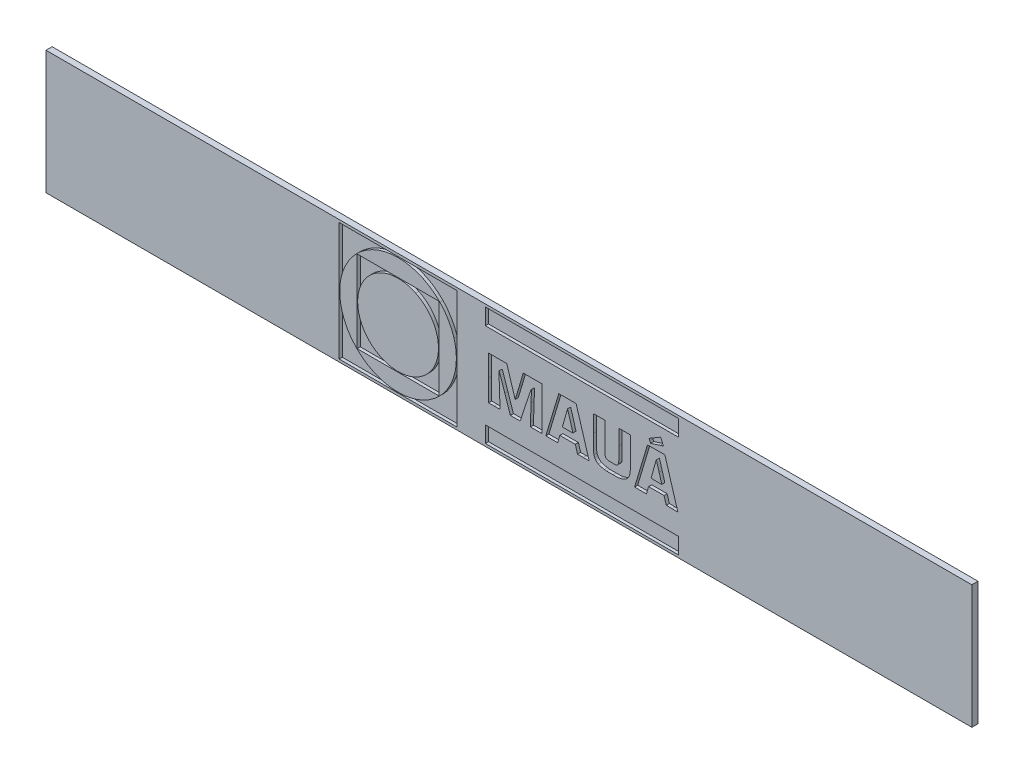
SolidWorks part; units mm, degrees
ref_plane "Front Plane" through (0, 0, 0) normal (0, 0, 1) x (1, 0, 0)
ref_plane "Top Plane" through (0, 0, 0) normal (0, 1, 0) x (1, 0, 0)
ref_plane "Right Plane" through (0, 0, 0) normal (1, 0, 0) x (0, 0, -1)
sketch "Model" plane through (0, 0, 0) normal (0, 0, 1) x (1, 0, 0)
  line L0 (-27.4995, 0.0001) -> (-27.4995, 9.5754)
  line L1 (-27.4995, 9.5754) -> (-17.9397, 9.5754)
  line L2 (-17.9397, 9.5754) -> (-8.3799, 9.5754)
  line L3 (-8.3799, 9.5754) -> (-8.3799, 0.0001)
  line L4 (-8.3799, 0.0001) -> (-8.3799, -9.5752)
  line L5 (-8.3799, -9.5752) -> (-17.9397, -9.5752)
  line L6 (-17.9397, -9.5752) -> (-27.4995, -9.5752)
  line L7 (-27.4995, -9.5752) -> (-27.4995, 0.0001)
  line L8 (-24.5819, -0.0154) -> (-24.5819, 6.6268)
  line L9 (-24.5819, 6.6268) -> (-17.9552, 6.6268)
  line L10 (-17.9552, 6.6268) -> (-11.3286, 6.6268)
  line L11 (-11.3286, 6.6268) -> (-11.3286, -0.0154)
  line L12 (-11.3286, -0.0154) -> (-11.3286, -6.6576)
  line L13 (-11.3286, -6.6576) -> (-17.9552, -6.6576)
  line L14 (-17.9552, -6.6576) -> (-24.5819, -6.6576)
  line L15 (-24.5819, -6.6576) -> (-24.5819, -0.0154)
  line L16 (-17.3141, -6.5322) -> (-17.3145, -6.5322)
  line L17 (-3.8173, -8.2716) -> (-3.8173, -6.968)
  line L18 (-3.8173, -6.968) -> (11.8416, -6.968)
  line L19 (11.8416, -6.968) -> (27.5004, -6.968)
  line L20 (27.5004, -6.968) -> (27.5004, -8.2716)
  line L21 (27.5004, -8.2716) -> (27.5004, -9.5752)
  line L22 (27.5004, -9.5752) -> (11.8416, -9.5752)
  line L23 (11.8416, -9.5752) -> (-3.8173, -9.5752)
  line L24 (-3.8173, -9.5752) -> (-3.8173, -8.2716)
  line L25 (13.6956, 0.6286) -> (13.6856, 3.3678)
  line L26 (13.6856, 3.3678) -> (14.6181, 3.3678)
  line L27 (14.6181, 3.3678) -> (15.5507, 3.3678)
  line L28 (15.5507, 3.3678) -> (15.5507, 0.9359)
  line L29 (17.8163, 0.939) -> (17.8164, 3.3678)
  line L30 (17.8164, 3.3678) -> (18.7476, 3.3678)
  line L31 (18.7476, 3.3678) -> (19.6787, 3.3678)
  line L32 (19.6787, 3.3678) -> (19.6787, 0.8267)
  line L33 (15.83, -3.6287) -> (15.83, -3.6289)
  line L34 (-3.2896, -0.1241) -> (-3.2896, 3.3678)
  line L35 (-3.2896, 3.3678) -> (-1.8168, 3.3678)
  line L36 (-1.8168, 3.3678) -> (-0.3439, 3.3678)
  line L37 (-0.3439, 3.3678) -> (-0.2812, 3.1582)
  line L38 (1.6785, 1.1795) -> (2.3115, 3.3678)
  line L39 (2.3115, 3.3678) -> (3.8254, 3.3678)
  line L40 (3.8254, 3.3678) -> (5.3393, 3.3678)
  line L41 (5.3393, 3.3678) -> (5.3314, -0.1163)
  line L42 (5.3314, -0.1163) -> (5.3236, -3.6004)
  line L43 (5.3236, -3.6004) -> (4.3976, -3.6086)
  line L44 (4.3976, -3.6086) -> (3.4716, -3.6168)
  line L45 (3.4716, -3.6168) -> (3.4957, -2.8481)
  line L46 (2.7012, -0.9465) -> (1.8195, -3.6158)
  line L47 (1.8195, -3.6158) -> (1.0264, -3.6153)
  line L48 (1.0264, -3.6153) -> (0.2333, -3.6148)
  line L49 (0.2333, -3.6148) -> (-0.6628, -0.9459)
  line L50 (-2.3688, -3.6155) -> (-3.2896, -3.6155)
  line L51 (-3.2896, -3.6155) -> (-3.2896, -0.1241)
  line L52 (9.4879, 3.3677) -> (10.8848, 3.3677)
  line L53 (10.8848, 3.3677) -> (11.9445, -0.1144)
  line L54 (12.0529, -3.6159) -> (11.121, -3.6159)
  line L55 (11.121, -3.6159) -> (10.9381, -3.0106)
  line L56 (10.9381, -3.0106) -> (10.7552, -2.4053)
  line L57 (10.7552, -2.4053) -> (9.5013, -2.4131)
  line L58 (9.5013, -2.4131) -> (8.2474, -2.4209)
  line L59 (8.2474, -2.4209) -> (8.077, -3.0184)
  line L60 (8.077, -3.0184) -> (7.9065, -3.6159)
  line L61 (7.9065, -3.6159) -> (6.9448, -3.6159)
  line L62 (6.9448, -3.6159) -> (5.9831, -3.6159)
  line L63 (5.9831, -3.6159) -> (6.0014, -3.5305)
  line L64 (23.8627, 3.3678) -> (25.2635, 3.3678)
  line L65 (25.2635, 3.3678) -> (25.3716, 3.0186)
  line L66 (26.4268, -3.6086) -> (25.4989, -3.6004)
  line L67 (25.4989, -3.6004) -> (25.315, -3.0029)
  line L68 (25.315, -3.0029) -> (25.1311, -2.4054)
  line L69 (25.1311, -2.4054) -> (23.8806, -2.4054)
  line L70 (23.8806, -2.4054) -> (22.63, -2.4054)
  line L71 (22.63, -2.4054) -> (22.5685, -2.6149)
  line L72 (20.3616, -3.6016) -> (20.3616, -3.6017)
  line L73 (23.893, -1.0397) -> (24.7618, -1.0397)
  line L74 (24.7618, -1.0397) -> (24.3326, 0.4537)
  line L75 (22.8219, 4.113) -> (22.6942, 4.3926)
  line L76 (22.6942, 4.3926) -> (23.2117, 4.6981)
  line L77 (-3.8173, 8.2563) -> (-3.8173, 9.5754)
  line L78 (-3.8173, 9.5754) -> (11.8416, 9.5754)
  line L79 (11.8416, 9.5754) -> (27.5004, 9.5754)
  line L80 (27.5004, 9.5754) -> (27.5004, 8.2563)
  line L81 (27.5004, 8.2563) -> (27.5004, 6.9372)
  line L82 (27.5004, 6.9372) -> (11.8416, 6.9372)
  line L83 (11.8416, 6.9372) -> (-3.8173, 6.9372)
  line L84 (-3.8173, 6.9372) -> (-3.8173, 8.2563)
  spline S0 degree 3 poles (-17.0662, -9.4193) (-15.2179, -9.2367) (-13.5182, -8.5448) (-12.0537, -7.3788) knots 0 0 0 0 1 1 1 1
  spline S1 degree 3 poles (-12.0537, -7.3788) (-11.6343, -7.045) (-10.9257, -6.339) (-10.5982, -5.9288) knots 0 0 0 0 1 1 1 1
  spline S2 degree 3 poles (-10.5982, -5.9288) (-8.6491, -3.4876) (-8.0249, -0.3347) (-8.8967, 2.6657) knots 0 0 0 0 1 1 1 1
  spline S3 degree 3 poles (-8.8967, 2.6657) (-9.3024, 4.062) (-10.1261, 5.4633) (-11.1833, 6.5557) knots 0 0 0 0 1 1 1 1
  spline S4 degree 3 poles (-11.1833, 6.5557) (-12.7357, 8.1599) (-14.7556, 9.1433) (-17.0086, 9.3919) knots 0 0 0 0 1 1 1 1
  spline S5 degree 3 poles (-17.0086, 9.3919) (-17.487, 9.4446) (-18.5269, 9.4359) (-19.0416, 9.3748) knots 0 0 0 0 1 1 1 1
  spline S6 degree 3 poles (-19.0416, 9.3748) (-21.9037, 9.035) (-24.4371, 7.4258) (-25.982, 4.9663) knots 0 0 0 0 1 1 1 1
  spline S7 degree 3 poles (-25.982, 4.9663) (-26.5362, 4.084) (-26.9635, 3.0463) (-27.1898, 2.0331) knots 0 0 0 0 1 1 1 1
  spline S8 degree 3 poles (-27.1898, 2.0331) (-27.4416, 0.9055) (-27.4745, -0.4505) (-27.2779, -1.5984) knots 0 0 0 0 1 1 1 1
  spline S9 degree 3 poles (-27.2779, -1.5984) (-27.0109, -3.1573) (-26.3504, -4.6283) (-25.3505, -5.8909) knots 0 0 0 0 1 1 1 1
  spline S10 degree 3 poles (-25.3505, -5.8909) (-25.0368, -6.287) (-24.2577, -7.0683) (-23.8681, -7.3775) knots 0 0 0 0 1 1 1 1
  spline S11 degree 3 poles (-23.8681, -7.3775) (-22.4629, -8.4924) (-20.8024, -9.1948) (-19.1192, -9.3865) knots 0 0 0 0 1 1 1 1
  spline S12 degree 3 poles (-19.1192, -9.3865) (-18.957, -9.405) (-18.7824, -9.4249) (-18.7312, -9.4309) knots 0 0 0 0 1 1 1 1
  spline S13 degree 3 poles (-18.7312, -9.4309) (-18.512, -9.4565) (-17.361, -9.4484) (-17.0662, -9.4193) knots 0 0 0 0 1 1 1 1
  spline S14 degree 3 poles (-17.3145, -6.5322) (-14.3242, -6.2313) (-11.8841, -3.8872) (-11.4699, -0.9178) knots 0 0 0 0 1 1 1 1
  spline S15 degree 3 poles (-11.4699, -0.9178) (-11.4081, -0.4744) (-11.4072, 0.4492) (-11.4679, 0.8786) knots 0 0 0 0 1 1 1 1
  spline S16 degree 3 poles (-11.4679, 0.8786) (-11.7766, 3.0505) (-13.1257, 4.9042) (-15.0993, 5.8684) knots 0 0 0 0 1 1 1 1
  spline S17 degree 3 poles (-15.0993, 5.8684) (-16.4346, 6.5208) (-17.9171, 6.6971) (-19.3826, 6.3779) knots 0 0 0 0 1 1 1 1
  spline S18 degree 3 poles (-19.3826, 6.3779) (-20.326, 6.1724) (-21.3782, 5.6557) (-22.1264, 5.0306) knots 0 0 0 0 1 1 1 1
  spline S19 degree 3 poles (-22.1264, 5.0306) (-25.0703, 2.5709) (-25.32, -1.7912) (-22.6746, -4.5435) knots 0 0 0 0 1 1 1 1
  spline S20 degree 3 poles (-22.6746, -4.5435) (-21.2819, -5.9924) (-19.2907, -6.7311) (-17.3141, -6.5322) knots 0 0 0 0 1 1 1 1
  spline S21 degree 3 poles (15.83, -3.6289) (15.7873, -3.6218) (15.6267, -3.6005) (15.4731, -3.5814) knots 0 0 0 0 1 1 1 1
  spline S22 degree 3 poles (15.4731, -3.5814) (15.1282, -3.5386) (14.7388, -3.4284) (14.4913, -3.3035) knots 0 0 0 0 1 1 1 1
  spline S23 degree 3 poles (14.4913, -3.3035) (14.1204, -3.1162) (13.91, -2.8375) (13.7739, -2.3531) knots 0 0 0 0 1 1 1 1
  spline S24 degree 3 poles (13.7739, -2.3531) (13.7064, -2.113) (13.7056, -2.0822) (13.6956, 0.6286) knots 0 0 0 0 1 1 1 1
  spline S25 degree 3 poles (15.5507, 0.9359) (15.5507, -0.8188) (15.5607, -1.5254) (15.5865, -1.6015) knots 0 0 0 0 1 1 1 1
  spline S26 degree 3 poles (15.5865, -1.6015) (15.6442, -1.7717) (15.7276, -1.8676) (15.8846, -1.9445) knots 0 0 0 0 1 1 1 1
  spline S27 degree 3 poles (15.8846, -1.9445) (16.0198, -2.0107) (16.0801, -2.0175) (16.6257, -2.028) knots 0 0 0 0 1 1 1 1
  spline S28 degree 3 poles (16.6257, -2.028) (17.1039, -2.0372) (17.253, -2.03) (17.3906, -1.9897) knots 0 0 0 0 1 1 1 1
  spline S29 degree 3 poles (17.3906, -1.9897) (17.5881, -1.9323) (17.7322, -1.7919) (17.7836, -1.607) knots 0 0 0 0 1 1 1 1
  spline S30 degree 3 poles (17.7836, -1.607) (17.805, -1.5298) (17.8162, -0.66) (17.8163, 0.939) knots 0 0 0 0 1 1 1 1
  spline S31 degree 3 poles (19.6787, 0.8267) (19.6787, -1.2943) (19.671, -1.7586) (19.6321, -1.9818) knots 0 0 0 0 1 1 1 1
  spline S32 degree 3 poles (19.6321, -1.9818) (19.4743, -2.8869) (19.0141, -3.3441) (18.0487, -3.5553) knots 0 0 0 0 1 1 1 1
  spline S33 degree 3 poles (18.0487, -3.5553) (17.7767, -3.6148) (17.6268, -3.6242) (16.8232, -3.6324) knots 0 0 0 0 1 1 1 1
  spline S34 degree 3 poles (16.8232, -3.6324) (16.3196, -3.6375) (15.8726, -3.6361) (15.83, -3.6287) knots 0 0 0 0 1 1 1 1
  spline S35 degree 3 poles (-0.2812, 3.1582) (0.4955, 0.5618) (0.9823, -1.0087) (1.0104, -1.0087) knots 0 0 0 0 1 1 1 1
  spline S36 degree 3 poles (1.0104, -1.0087) (1.0303, -1.0087) (1.3208, -0.0571) (1.6785, 1.1795) knots 0 0 0 0 1 1 1 1
  spline S37 degree 3 poles (3.4957, -2.8481) (3.5089, -2.4253) (3.5503, -1.2274) (3.5876, -0.1861) knots 0 0 0 0 1 1 1 1
  spline S38 degree 3 poles (3.5876, -0.1861) (3.6249, 0.8552) (3.6525, 1.7107) (3.6489, 1.715) knots 0 0 0 0 1 1 1 1
  spline S39 degree 3 poles (3.6489, 1.715) (3.6071, 1.7644) (3.4606, 1.3529) (2.7012, -0.9465) knots 0 0 0 0 1 1 1 1
  spline S40 degree 3 poles (-0.6628, -0.9459) (-1.1557, 0.5221) (-1.5721, 1.7231) (-1.5882, 1.7231) knots 0 0 0 0 1 1 1 1
  spline S41 degree 3 poles (-1.5882, 1.7231) (-1.6196, 1.7231) (-1.6153, 1.5605) (-1.5011, -1.644) knots 0 0 0 0 1 1 1 1
  spline S42 degree 3 poles (-1.5011, -1.644) (-1.4628, -2.7192) (-1.4352, -3.6026) (-1.4397, -3.6072) knots 0 0 0 0 1 1 1 1
  spline S43 degree 3 poles (-1.4397, -3.6072) (-1.4443, -3.6117) (-1.8624, -3.6155) (-2.3688, -3.6155) knots 0 0 0 0 1 1 1 1
  spline S44 degree 3 poles (6.0014, -3.5305) (6.0295, -3.3996) (8.0606, 3.3372) (8.0768, 3.3535) knots 0 0 0 0 1 1 1 1
  spline S45 degree 3 poles (8.0768, 3.3535) (8.0847, 3.3613) (8.7197, 3.3677) (9.4879, 3.3677) knots 0 0 0 0 1 1 1 1
  spline S46 degree 3 poles (11.9445, -0.1144) (12.5274, -2.0295) (12.9999, -3.6008) (12.9945, -3.6062) knots 0 0 0 0 1 1 1 1
  spline S47 degree 3 poles (12.9945, -3.6062) (12.9892, -3.6115) (12.5655, -3.6159) (12.0529, -3.6159) knots 0 0 0 0 1 1 1 1
  spline S48 degree 3 poles (10.3673, -1.0164) (10.3673, -0.9309) (9.5113, 1.962) (9.495, 1.9316) knots 0 0 0 0 1 1 1 1
  spline S49 degree 3 poles (9.495, 1.9316) (9.4757, 1.8956) (8.6601, -0.9921) (8.6601, -1.0245) knots 0 0 0 0 1 1 1 1
  spline S50 degree 3 poles (8.6601, -1.0245) (8.6601, -1.0328) (9.0442, -1.0397) (9.5137, -1.0397) knots 0 0 0 0 1 1 1 1
  spline S51 degree 3 poles (9.5137, -1.0397) (9.9832, -1.0397) (10.3673, -1.0292) (10.3673, -1.0164) knots 0 0 0 0 1 1 1 1
  spline S52 degree 3 poles (20.3616, -3.6017) (20.3616, -3.5739) (22.4378, 3.3436) (22.4497, 3.3556) knots 0 0 0 0 1 1 1 1
  spline S53 degree 3 poles (22.4497, 3.3556) (22.4564, 3.3623) (23.0922, 3.3678) (23.8627, 3.3678) knots 0 0 0 0 1 1 1 1
  spline S54 degree 3 poles (25.3716, 3.0186) (25.9086, 1.2843) (27.3791, -3.5924) (27.3684, -3.6031) knots 0 0 0 0 1 1 1 1
  spline S55 degree 3 poles (27.3684, -3.6031) (27.3608, -3.6107) (26.9371, -3.6131) (26.4268, -3.6086) knots 0 0 0 0 1 1 1 1
  spline S56 degree 3 poles (22.5685, -2.6149) (22.5347, -2.7301) (22.4576, -2.9975) (22.3972, -3.2091) knots 0 0 0 0 1 1 1 1
  spline S57 degree 3 poles (22.3972, -3.2091) (22.3367, -3.4207) (22.2823, -3.5988) (22.2763, -3.6049) knots 0 0 0 0 1 1 1 1
  spline S58 degree 3 poles (22.2763, -3.6049) (22.2599, -3.6213) (20.3616, -3.6182) (20.3616, -3.6016) knots 0 0 0 0 1 1 1 1
  spline S59 degree 3 poles (24.3326, 0.4537) (24.0965, 1.275) (23.8969, 1.9534) (23.889, 1.9613) knots 0 0 0 0 1 1 1 1
  spline S60 degree 3 poles (23.889, 1.9613) (23.8724, 1.9779) (23.8886, 2.0335) (23.4171, 0.3415) knots 0 0 0 0 1 1 1 1
  spline S61 degree 3 poles (23.4171, 0.3415) (23.2174, -0.3755) (23.0472, -0.9796) (23.0391, -1.0009) knots 0 0 0 0 1 1 1 1
  spline S62 degree 3 poles (23.0391, -1.0009) (23.0274, -1.0314) (23.2108, -1.0397) (23.893, -1.0397) knots 0 0 0 0 1 1 1 1
  spline S63 degree 3 poles (23.2117, 4.6981) (24.4506, 5.4295) (24.5912, 5.5112) (24.5965, 5.5028) knots 0 0 0 0 1 1 1 1
  spline S64 degree 3 poles (24.5965, 5.5028) (24.6603, 5.4019) (25.0397, 4.4957) (25.024, 4.4817) knots 0 0 0 0 1 1 1 1
  spline S65 degree 3 poles (25.024, 4.4817) (25.0016, 4.4618) (23.0123, 3.8333) (22.9716, 3.8333) knots 0 0 0 0 1 1 1 1
  spline S66 degree 3 poles (22.9716, 3.8333) (22.9595, 3.8333) (22.8921, 3.9592) (22.8219, 4.113) knots 0 0 0 0 1 1 1 1
sketch "Sketch2" plane through (0, 0, 0) normal (0, 0, 1) x (1, 0, 0)
  line L1 (75, 10) -> (-75, 10)
  line L2 (75, 10) -> (75, -10)
  line L3 (75, -10) -> (-75, -10)
  line L4 (-75, 10) -> (-75, -10)
  line L5 (75, 10) -> (-75, -10) construction
  line L6 (75, -10) -> (-75, 10) construction
  point P0 (0, 0)
  dimension "D1" = 20
  dimension "D2" = 150
extrude "Boss-Extrude1" add sketch "Sketch2" against normal blind 1
extrude "Cut-Extrude2" cut sketch "Model" against normal blind 0.5 contours L84 L83 L82 L81 L80 L79 L78 L77 | L24 L23 L22 L21 L20 L19 L18 L17 | S58 S57 S56 L71 L70 L69 L68 L67 L66 S55 S54 L65 L64 S53 S52 S62 S61 S60 S59 L74 L73 | S43 S42 S41 S40 L49 L48 L47 L46 S39 S38 S37 L45 L44 L43 L42 L41 L40 L39 L38 S36 S35 L37 L36 L35 L34 L51 L50 | S47 S46 L53 L52 S45 S44 L63 L62 L61 L60 L59 L58 L57 L56 L55 L54 S51 S50 S49 S48 | S34 S33 S32 S31 L32 L31 L30 L29 S30 S29 S28 S27 S26 S25 L28 L27 L26 L25 S24 S23 S22 S21 L33 | S66 S65 S64 S63 L76 L75 | L7 L6 L5 L4 L3 L2 L1 L0 S13 S12 S11 S10 S9 S8 S7 S6 S5 S4 S3 S2 S1 S0 | L15 L14 L13 L12 L11 L10 L9 L8 S20 S19 S18 S17 S16 S15 S14 L16
